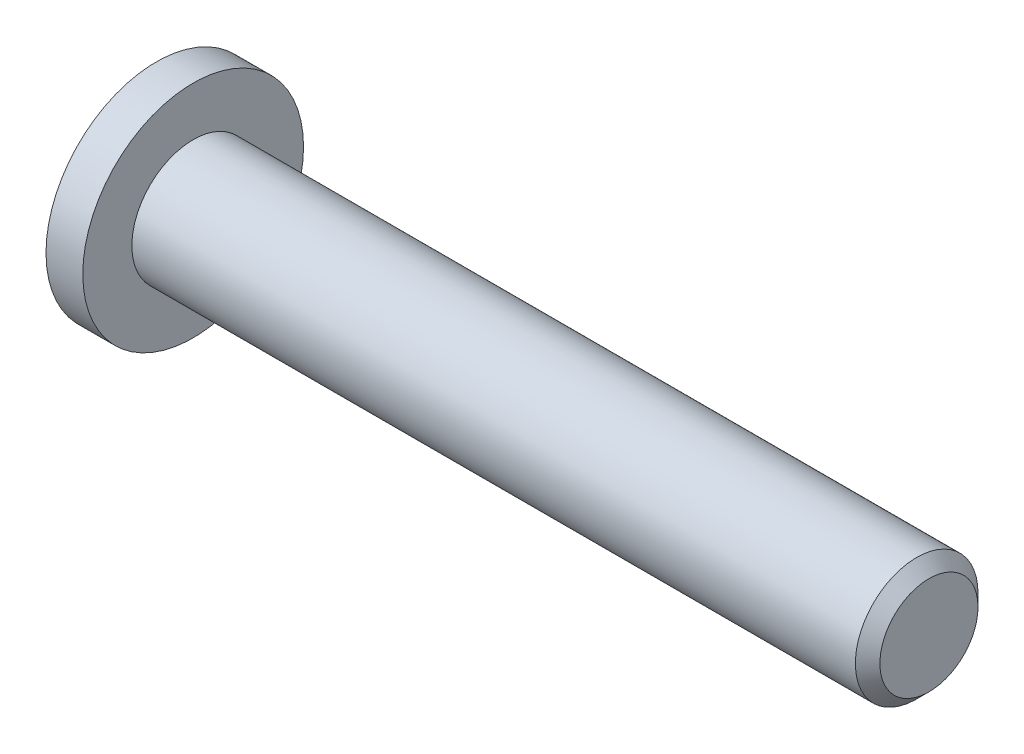
SolidWorks part; units mm, degrees
material "AISI 304"
ref_plane "Front Plane" through (0, 0, 0) normal (0, 0, 1) x (1, 0, 0)
ref_plane "Top Plane" through (0, 0, 0) normal (0, 1, 0) x (1, 0, 0)
ref_plane "Right Plane" through (0, 0, 0) normal (1, 0, 0) x (0, 0, -1)
sketch "Sketch1" plane through (0, 0, 0) normal (1, 0, 0) x (0, 0, -1)
  circle A0 centre (0, 0) radius 4.5
  dimension "D1" = 9
extrude "Head" add sketch "Sketch1" along normal blind 1.5
sketch "Sketch2" plane through (1.5, 0, 0) normal (1, 0, 0) x (0, 0, -1)
  circle A0 centre (0, 0) radius 2.5
  dimension "D1" = 5
extrude "Body" add sketch "Sketch2" along normal blind 30
cosmetic thread "Cosmetic Thread2" parameters "D1"=28, "D2"=4.11
sketch "Sketch3" plane through (0, 0, 0) normal (-1, 0, 0) x (0, 0, 1)
  line L1 (0, 1.7321) -> (-1.5, 0.866)
  line L2 (-1.5, 0.866) -> (-1.5, -0.866)
  line L3 (-1.5, -0.866) -> (0, -1.7321)
  line L4 (0, -1.7321) -> (1.5, -0.866)
  line L5 (1.5, -0.866) -> (1.5, 0.866)
  line L6 (1.5, 0.866) -> (0, 1.7321)
  circle A0 centre (0, 0) radius 1.5 construction
  dimension "D1" = 3
extrude "Drive" cut sketch "Sketch3" against normal blind 3
chamfer "Chamfer1" distance 0.5 angle 45 1 edges at (31.5, 0, -2.5)
